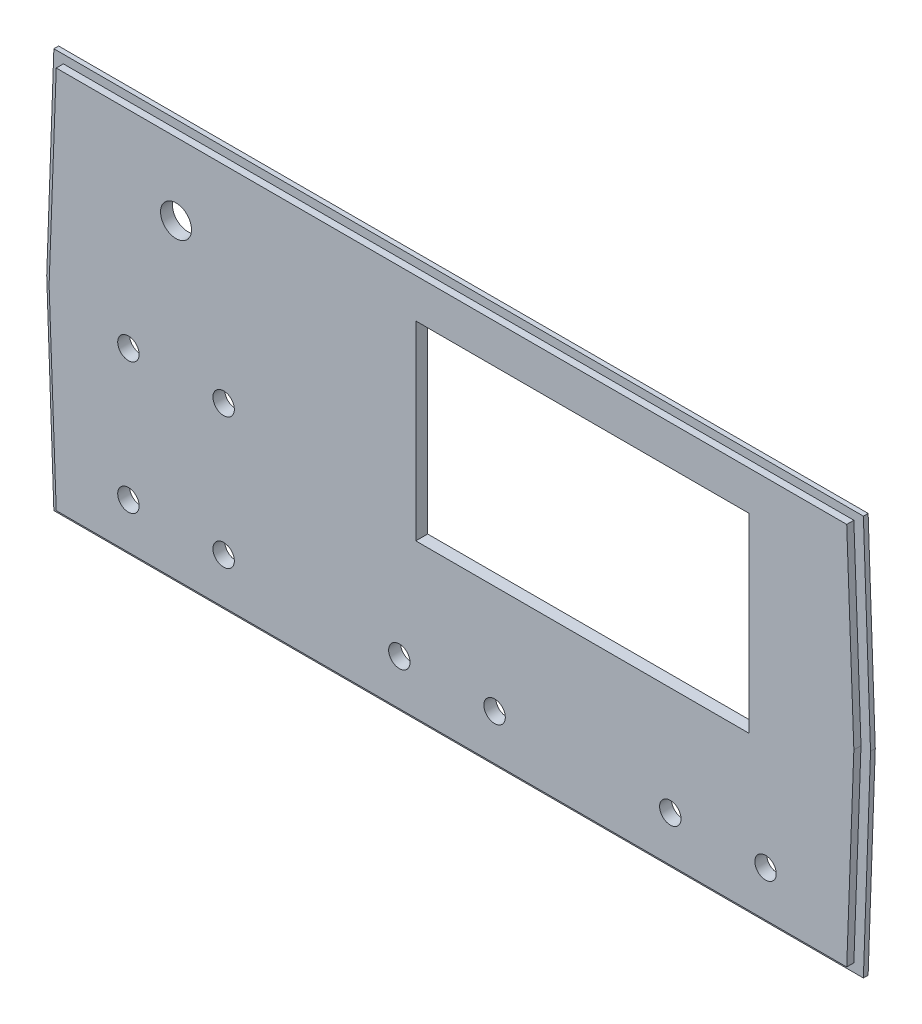
SolidWorks part; units mm, degrees
ref_plane "Front Plane" through (0, 0, 0) normal (0, 0, 1) x (1, 0, 0)
ref_plane "Top Plane" through (0, 0, 0) normal (0, 1, 0) x (1, 0, 0)
ref_plane "Right Plane" through (0, 0, 0) normal (1, 0, 0) x (0, 0, -1)
sketch "Sketch1" plane through (0, 0, 0) normal (0, 0, 1) x (1, 0, 0)
  line L1 (-85, 42) -> (85, 42)
  line L3 (-85, -42) -> (85, -42)
  line L5 (-85, 42) -> (85, -42) construction
  line L6 (-85, -42) -> (85, 42) construction
  line L7 (-86.5, 0) -> (-85, -42)
  line L8 (-85, 42) -> (-86.5, 0)
  line L9 (85, -42) -> (86.5, 0)
  line L10 (85, 42) -> (86.5, 0)
  point P0 (0, 0)
  dimension "D1" = 170
  dimension "D2" = 84
  dimension "D3" = 173
extrude "Boss-Extrude1" add sketch "Sketch1" along normal blind 1
sketch "Sketch2" plane through (0, 0, 1) normal (0, 0, 1) x (1, 0, 0)
  line L0 (-84.5, 0) -> (84.5, 0) construction
  line L1 (-83, 40.25) -> (83, 40.25)
  line L3 (-83, -40.25) -> (83, -40.25)
  line L5 (-83, 40.25) -> (83, -40.25) construction
  line L6 (-83, -40.25) -> (83, 40.25) construction
  line L7 (-83, -40.25) -> (-84.5, 0)
  line L8 (-84.5, 0) -> (-83, 40.25)
  line L9 (83, -40.25) -> (84.5, 0)
  line L10 (84.5, 0) -> (83, 40.25)
  point P0 (0, 0)
  dimension "D1" = 166
  dimension "D2" = 80.5
  dimension "D3" = 169
extrude "Boss-Extrude2" add sketch "Sketch2" along normal blind 1.5
sketch "Sketch3" plane through (0, 0, 0) normal (0, 0, -1) x (-1, 0, 0)
  line L0 (-85, 42) -> (85, 42) construction
  line L1 (-62.5, 32) -> (7.5, 32)
  line L2 (-62.5, 32) -> (-62.5, -8)
  line L3 (-62.5, -8) -> (7.5, -8)
  line L4 (7.5, 32) -> (7.5, -8)
  line L5 (-62.5, 32) -> (7.5, -8) construction
  line L6 (-62.5, -8) -> (7.5, 32) construction
  line L11 (-67, 40.5) -> (12, -16.5) construction
  line L12 (-67, -16.5) -> (12, 40.5) construction
  point P0 (-27.5, 12)
  point P5 (-27.5, 12)
  dimension "D1" = 40
  dimension "D2" = 70
  dimension "D5" = 30
  dimension "D6" = 57.5
extrude "Cut-Extrude1" cut sketch "Sketch3" against normal blind 10
sketch "Sketch4" plane through (0, 0, 0) normal (0, 0, -1) x (-1, 0, 0)
  line L0 (57.845, -30.7059) -> (57.845, 43.0441) construction
  line L1 (40.845, -23.2059) -> (74.845, -23.2059) construction
  line L2 (40.845, -23.2059) -> (40.845, -38.2059) construction
  line L3 (40.845, -38.2059) -> (74.845, -38.2059) construction
  line L4 (74.845, -23.2059) -> (74.845, -38.2059) construction
  line L5 (67.845, -3.142) -> (47.845, -3.142) construction
  line L6 (-38.955, -23.2059) -> (-72.9544, -23.2059) construction
  line L7 (40.845, -23.2059) -> (74.845, -38.2059) construction
  line L8 (40.845, -38.2059) -> (74.845, -23.2059) construction
  line L9 (-72.9544, -30.7059) -> (74.845, -30.7059) construction
  line L10 (-16.0547, -23.2059) -> (17.9453, -23.2059) construction
  line L11 (-16.0547, -23.2059) -> (-16.0547, -38.2059) construction
  line L12 (-16.0547, -38.2059) -> (17.9453, -38.2059) construction
  line L13 (17.9453, -23.2059) -> (17.9453, -38.2059) construction
  line L14 (-16.0547, -23.2059) -> (17.9453, -38.2059) construction
  line L15 (-16.0547, -38.2059) -> (17.9453, -23.2059) construction
  line L16 (-66.655, -20.4559) -> (-85.3871, -20.4559) construction
  line L17 (-38.955, -23.2059) -> (-38.955, -38.2059) construction
  line L18 (-38.955, -38.2059) -> (-72.9544, -38.2059) construction
  line L19 (-72.9544, -23.2059) -> (-72.9544, -38.2059) construction
  line L20 (-38.955, -23.2059) -> (-72.9544, -38.2059) construction
  line L21 (-38.955, -38.2059) -> (-72.9544, -23.2059) construction
  line L22 (40.845, 4.358) -> (74.845, 4.358) construction
  line L23 (40.845, 4.358) -> (40.845, -10.642) construction
  line L24 (40.845, -10.642) -> (74.845, -10.642) construction
  line L25 (74.845, 4.358) -> (74.845, -10.642) construction
  line L26 (40.845, 4.358) -> (74.845, -10.642) construction
  line L27 (40.845, -10.642) -> (74.845, 4.358) construction
  circle A0 centre (-65.9547, -30.7059) radius 2.25
  circle A1 centre (-45.9547, -30.7059) radius 2.25
  circle A2 centre (-9.0547, -30.7059) radius 2.25
  circle A3 centre (10.9453, -30.7059) radius 2.25
  circle A4 centre (47.845, -30.7059) radius 2.25
  circle A5 centre (67.845, -30.7059) radius 2.25
  circle A6 centre (67.845, -3.142) radius 2.25
  circle A7 centre (67.845, -3.142) radius 2.25
  circle A8 centre (57.845, 25.0441) radius 3.25
  circle A9 centre (47.845, -3.142) radius 2.25
  point P0 (-5.0689, 2.0147)
  point P1 (0.9453, -30.7059)
  point P2 (57.845, -30.7059)
  point P7 (-55.9547, -30.7059)
  point P14 (57.845, -3.142)
  point P32 (-55.9547, -30.7059)
  point P33 (-55.9547, -30.7059)
  dimension "D3" = 4.5
  dimension "D4" = 4.5
  dimension "D5" = 4.5
  dimension "D6" = 4.5
  dimension "D7" = 4.5
  dimension "D8" = 4.5
  dimension "D11" = 6.5
  dimension "D16" = 4.5
  dimension "D17" = 4.5
  dimension "D20" = 4.5
  dimension "D1" = 34
  dimension "D2" = 15
  dimension "D9" = 10
  dimension "D10" = 10
  dimension "D12" = 56.8997
  dimension "D13" = 56.9
  dimension "D14" = 10
  dimension "D15" = 10
  dimension "D18" = 10
  dimension "D19" = 10
  dimension "D21" = 10
extrude "Cut-Extrude3" cut sketch "Sketch4" against normal blind 10 contours A0 | A1 | A2 | A3 | A4 | A5 | A6 | A9 | A8
